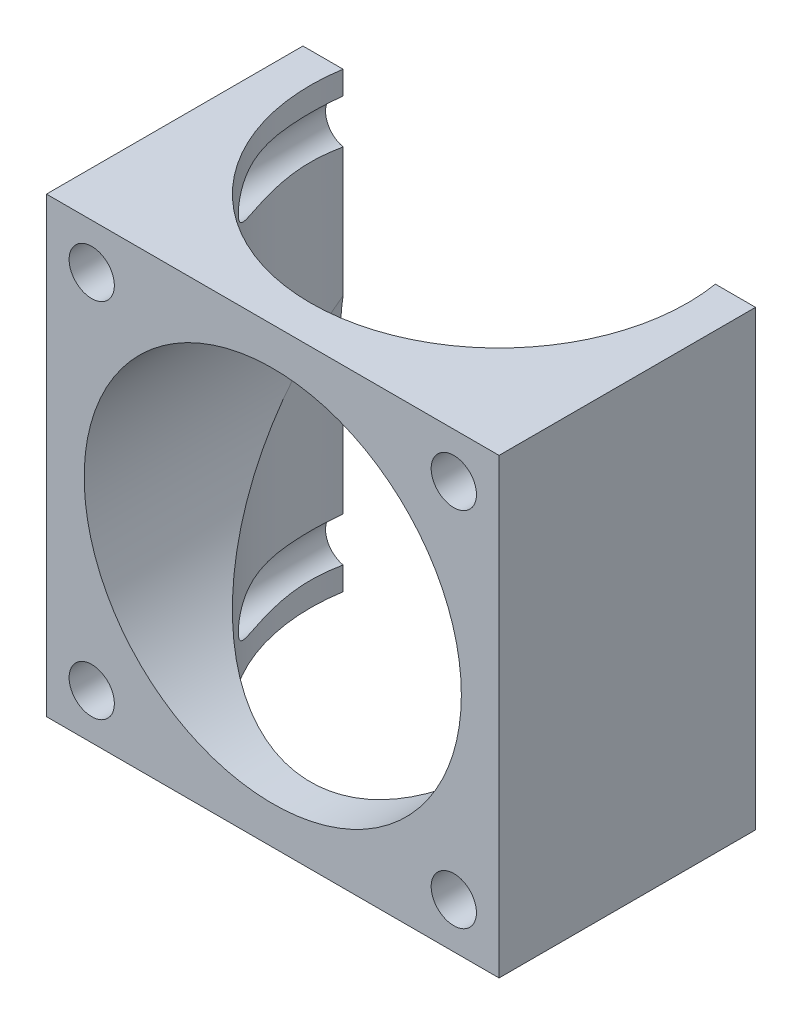
SolidWorks part; units mm, degrees
material "ABS"
ref_plane "Přední rovina" through (0, 0, 0) normal (0, 0, 1) x (1, 0, 0)
ref_plane "Horní rovina" through (0, 0, 0) normal (0, 1, 0) x (1, 0, 0)
ref_plane "Pravá rovina" through (0, 0, 0) normal (1, 0, 0) x (0, 0, -1)
sketch "Skica1" plane through (0, 0, 0) normal (0, 1, 0) x (1, 0, 0)
  line L0 (-12.5, 0) -> (-15, 0) construction
  line L1 (12.5, 0) -> (15, 0) construction
  line L2 (-15, 0) -> (-15, 2)
  line L3 (15, 0) -> (15, 2)
  line L4 (-15, 0) -> (-15, -15)
  line L5 (15, 0) -> (15, -15)
  line L6 (-15, -15) -> (15, -15)
  line L7 (-15, 2) -> (15, 2)
  circle A0 centre (0, 0) radius 12.5
  dimension "D1" = 25
  dimension "D6" = 30
  dimension "D3" = 2
  dimension "D4" = 15
  dimension "D5" = 15
extrude "Přidat vysunutím1" add sketch "Skica1" along normal blind 30 contours A0 L7 L2 L4 L6 L5 L3
sketch "Skica2" plane through (0, 0, 15) normal (0, 0, 1) x (1, 0, 0)
  circle A0 centre (0, 15) radius 12.5
  dimension "D1" = 25
extrude "Odebrat vysunutím1" cut sketch "Skica2" against normal blind 30
sketch "Skica3" plane through (0, 0, 15) normal (0, 0, 1) x (1, 0, 0)
  line L0 (0, 30) -> (-12, 30) construction
  line L1 (-15, 30) -> (15, 30) construction
  line L2 (-15, 15) -> (-15, 27) construction
  line L3 (-15, 30) -> (-15, 0) construction
  circle A0 centre (-12, 27) radius 1.5
  circle A1 centre (12, 27) radius 1.5
  circle A2 centre (12, 3) radius 1.5
  circle A3 centre (-12, 3) radius 1.5
  dimension "D1" = 2
  dimension "D2" = 2
extrude "Odebrat vysunutím2" cut sketch "Skica3" against normal blind 30
